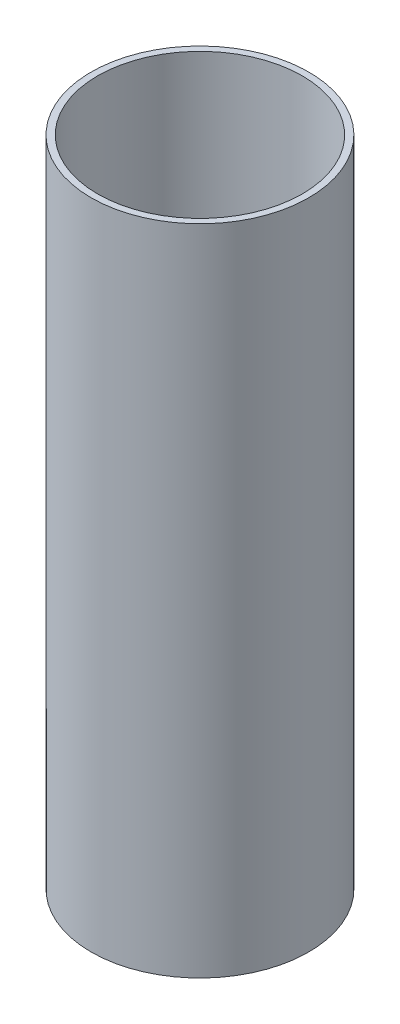
SolidWorks part; units mm, degrees
ref_plane "前视基准面" through (0, 0, 0) normal (0, 0, 1) x (1, 0, 0)
ref_plane "上视基准面" through (0, 0, 0) normal (0, 1, 0) x (1, 0, 0)
ref_plane "右视基准面" through (0, 0, 0) normal (1, 0, 0) x (0, 0, -1)
sketch "草图1" plane through (0, 0, 0) normal (0, 1, 0) x (1, 0, 0)
  circle A0 centre (0, 0) radius 23.5
  circle A1 centre (0, 0) radius 25
  dimension "D1" = 47
  dimension "D2" = 50
extrude "50PVC" add sketch "草图1" along normal blind 150
